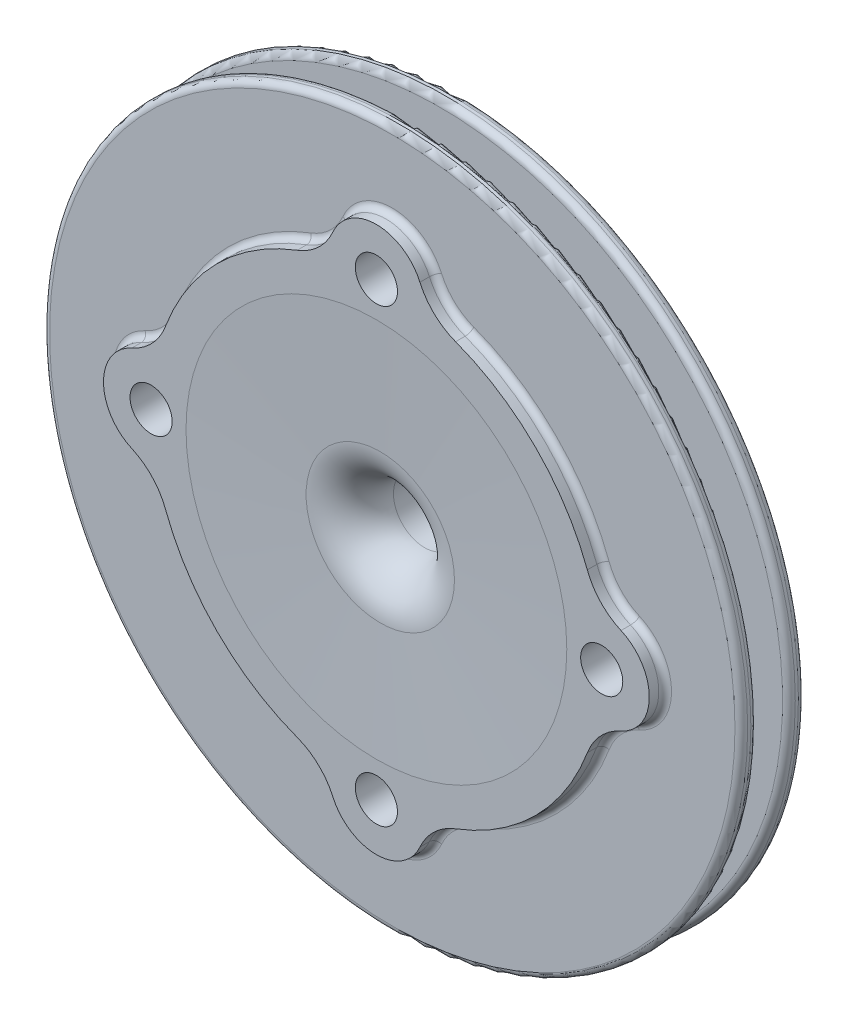
SolidWorks part; units mm, degrees
material "Cast Alloy Steel"
ref_plane "Front Plane" through (0, 0, 0) normal (0, 0, 1) x (1, 0, 0)
ref_plane "Top Plane" through (0, 0, 0) normal (0, 1, 0) x (1, 0, 0)
ref_plane "Right Plane" through (0, 0, 0) normal (1, 0, 0) x (0, 0, -1)
sketch "Diamond Base Sketch" plane through (0, 0, 0) normal (0, 0, 1) x (1, 0, 0)
  arc A0 (-15.8513, 42.2066) -> (-42.2066, 15.8513) centre (0, 0) ccw
  arc A1 (8.707, 48.9467) -> (-8.707, 48.9467) centre (0, 45.085) ccw
  arc A2 (48.9467, -8.707) -> (48.9467, 8.707) centre (45.085, 0) ccw
  arc A3 (-8.707, -48.9467) -> (8.707, -48.9467) centre (0, -45.085) ccw
  arc A4 (-48.9467, 8.707) -> (-48.9467, -8.707) centre (-45.085, 0) ccw
  arc A5 (-42.2066, -15.8513) -> (-15.8513, -42.2066) centre (0, 0) ccw
  arc A6 (42.2066, 15.8513) -> (15.8513, 42.2066) centre (0, 0) ccw
  arc A7 (15.8513, -42.2066) -> (42.2066, -15.8513) centre (0, 0) ccw
  arc A8 (48.9467, -8.707) -> (42.2066, -15.8513) centre (54.0957, -20.3164) ccw
  arc A9 (-8.707, -48.9467) -> (-15.8513, -42.2066) centre (-20.3164, -54.0957) ccw
  arc A10 (48.9467, 8.707) -> (42.2066, 15.8513) centre (54.0957, 20.3164) cw
  arc A11 (-8.707, 48.9467) -> (-15.8513, 42.2066) centre (-20.3164, 54.0957) cw
  arc A12 (-48.9467, 8.707) -> (-42.2066, 15.8513) centre (-54.0957, 20.3164) ccw
  arc A13 (-48.9467, -8.707) -> (-42.2066, -15.8513) centre (-54.0957, -20.3164) cw
  arc A14 (8.707, 48.9467) -> (15.8513, 42.2066) centre (20.3164, 54.0957) ccw
  arc A15 (8.707, -48.9467) -> (15.8513, -42.2066) centre (20.3164, -54.0957) cw
  point P14 (0, 0)
  point P24 (44.0788, 9.4717)
  point P31 (-44.0788, -9.4717)
  point P36 (9.4717, -44.0788)
  dimension "D1" = 90.17
  dimension "D2" = 19.05
  dimension "D4" = 12.7
  dimension "D5" = 12.7
  dimension "D3" = 4
extrude "Diamond Base Extrude" add sketch "Diamond Base Sketch" along normal mid plane 19.05
ref_plane "Offset Front Plane" through (0, 0, 6.35) normal (0, 0, 1) x (1, 0, 0)
sketch "Circular Base Sketch" plane through (0, 0, 6.35) normal (0, 0, 1) x (1, 0, 0)
  circle A0 centre (0, 0) radius 69.85
  dimension "D1" = 139.7
extrude "Circular Base Extrude" add sketch "Circular Base Sketch" against normal blind 3.175
ref_plane "Offset Rear Plane" through (0, 0, -6.35) normal (0, 0, -1) x (-1, 0, 0)
sketch "Rear Base Sketch" plane through (0, 0, -6.35) normal (0, 0, -1) x (-1, 0, 0)
  circle A0 centre (0, 0) radius 69.85
  dimension "D1" = 139.7
extrude "Rear Base Extrude" add sketch "Rear Base Sketch" against normal blind 3.175
hole_wizard "M14x1.5 Center Hole" positions "Center Hole Sketch" profile "Center Hole Depth" tap size "M14x1.5" standard "ANSI Metric" end condition through all
sketch "Center Hole Sketch" plane through (0, 0, 9.525) normal (0, 0, 1) x (1, 0, 0)
  point P0 (0, 0)
sketch "Center Hole Depth" plane through (0, 0, 9.525) normal (1, 0, 0) x (0, -1, 0)
  line L0 (0, 0) -> (0, 19.05)
  line L1 (0, 19.05) -> (6.25, 19.05)
  line L2 (6.25, 19.05) -> (6.25, 0)
  line L5 (6.25, 0) -> (0, 0)
  line L11 (0, -6.35) -> (0, 107.95) construction
  dimension "Thru Tap Drill Dia." = 12.5
  dimension "Thru Tap Drill Depth" = 19.05
cosmetic thread "Center Hole Thread" parameters "D2"=14
sketch "Circular Sketch" plane through (0, 0, 9.525) normal (0, 0, 1) x (1, 0, 0)
  circle A0 centre (-45.085, 0) radius 4.2164
  dimension "D1" = 8.4328
extrude "Circular Cut" cut sketch "Circular Sketch" against normal through all
pattern_circular "Circular Pattern" count 4 over 360 about axis through (0, 0, 0) along (0, 0, 1) of "Circular Cut"
sketch "Sketch12" plane through (0, 0, 0) normal (0, 1, 0) x (1, 0, 0)
  line L0 (0, 0) -> (0, -9.525) construction
  line L1 (-8.707, -9.525) -> (8.707, -9.525) construction
  line L2 (0, -8.255) -> (38.1, -9.525)
  line L3 (15.8513, -9.525) -> (42.2066, -9.525) construction
  line L4 (38.1, -9.525) -> (0, -9.525)
  line L5 (0, -9.525) -> (0, -8.255)
  dimension "D1" = 38.1
  dimension "D2" = 1.27
revolve "Triangular Revolve Cut" cut sketch "Sketch12" angle 360 about L0
sketch "Triangular Sketch" plane through (0, 0, 0) normal (0, 1, 0) x (1, 0, 0)
  line L0 (32.6738, -9.525) -> (0, -7.603)
  line L1 (15.8513, -9.525) -> (42.2066, -9.525) construction
  line L2 (0, -7.603) -> (0, -9.525)
  line L3 (-8.707, -9.525) -> (8.707, -9.525) construction
  line L4 (0, -9.525) -> (32.6738, -9.525)
  point P4 (0, 0)
  dimension "D1" = 32.6738
  dimension "D2" = 3.367
fillet "Center Fillet" radius 8.89 1 edges at (6.25, 0, 8.4633)
fillet "Peripheral Fillet" radius 1.27 68 edges at (-69.85, 0, -6.35) (-54.61, 0, -6.35) (-31.8799, 31.8799, -6.35) (0, 54.61, -6.35) (31.8799, 31.8799, -6.35) (54.61, 0, -6.35) (31.8799, -31.8799, -6.35) (0, -54.61, -6.35) (-31.8799, -31.8799, -6.35) (-69.85, 0, -3.175) (31.8799, -31.8799, -3.175) (54.61, 0, -3.175) (31.8799, 31.8799, -3.175) (0, 54.61, -3.175) (-31.8799, 31.8799, -3.175) (-54.61, 0, -3.175) (-31.8799, -31.8799, -3.175) (0, -54.61, -3.175) (69.85, 0, 3.175) (-31.8799, 31.8799, 3.175) (0, 54.61, 3.175) (31.8799, 31.8799, 3.175) (54.61, 0, 3.175) (31.8799, -31.8799, 3.175) (0, -54.61, 3.175) (-31.8799, -31.8799, 3.175) (-54.61, 0, 3.175) (69.85, 0, 6.35) (0, -54.61, 6.35) (31.8799, -31.8799, 6.35) (54.61, 0, 6.35) (31.8799, 31.8799, 6.35) (0, 54.61, 6.35) (-31.8799, 31.8799, 6.35) (-54.61, 0, 6.35) (-31.8799, -31.8799, 6.35) (11.6012, -44.8581, -6.35) (-11.6012, -44.8581, -6.35) (-44.8581, -11.6012, -6.35) (-44.8581, 11.6012, -6.35) (-11.6012, 44.8581, -6.35) (11.6012, 44.8581, -6.35) (44.8581, 11.6012, -6.35) (44.8581, -11.6012, -6.35) (44.8581, 11.6012, -3.175) (11.6012, 44.8581, -3.175) (-11.6012, 44.8581, -3.175) (-44.8581, 11.6012, -3.175) (-44.8581, -11.6012, -3.175) (-11.6012, -44.8581, -3.175) (11.6012, -44.8581, -3.175) (44.8581, -11.6012, -3.175) (11.6012, -44.8581, 3.175) (-11.6012, -44.8581, 3.175) (-44.8581, -11.6012, 3.175) (-44.8581, 11.6012, 3.175) (-11.6012, 44.8581, 3.175) (11.6012, 44.8581, 3.175) (44.8581, 11.6012, 3.175) (44.8581, -11.6012, 3.175) (44.8581, 11.6012, 6.35) (11.6012, 44.8581, 6.35) (-11.6012, 44.8581, 6.35) (-44.8581, 11.6012, 6.35) (-44.8581, -11.6012, 6.35) (-11.6012, -44.8581, 6.35) (11.6012, -44.8581, 6.35) (44.8581, -11.6012, 6.35)
